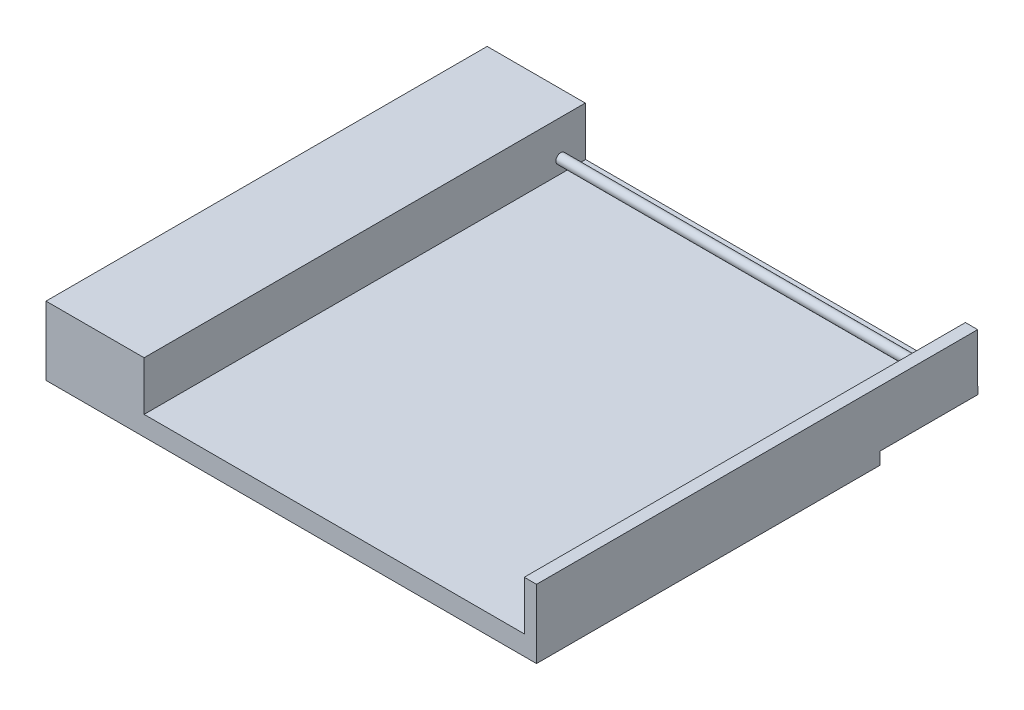
SolidWorks part; units mm, degrees
ref_plane "Front Plane" through (0, 0, 0) normal (0, 0, 1) x (1, 0, 0)
ref_plane "Top Plane" through (0, 0, 0) normal (0, 1, 0) x (1, 0, 0)
ref_plane "Right Plane" through (0, 0, 0) normal (1, 0, 0) x (0, 0, -1)
sketch "Sketch1" plane through (0, 0, 0) normal (0, 1, 0) x (1, 0, 0)
  line L1 (-100, -90) -> (100, -90)
  line L2 (-100, -90) -> (-100, 90)
  line L3 (-100, 90) -> (100, 90)
  line L4 (100, -90) -> (100, 90)
  line L5 (-100, -90) -> (100, 90) construction
  line L6 (-100, 90) -> (100, -90) construction
  point P0 (0, 0)
  dimension "D1" = 200
  dimension "D2" = 180
extrude "Boss-Extrude1" add sketch "Sketch1" along normal blind 3
sketch "Sketch2" plane through (0, 0, 0) normal (0, -1, 0) x (1, 0, 0)
  line L0 (-100, 90) -> (100, 90)
  line L1 (-100, 90) -> (-100, -50)
  line L2 (100, 90) -> (100, -50)
  line L3 (-100, -50) -> (100, -50)
  dimension "D1" = 140
extrude "Boss-Extrude2" add sketch "Sketch2" along normal blind 5
sketch "Sketch6" plane through (0, 3, 0) normal (0, 1, 0) x (1, 0, 0)
  line L0 (-100, -90) -> (100, -90)
  line L1 (-100, -90) -> (-100, 89.8697)
  line L2 (100, -90) -> (100, 89.8697)
  line L3 (-100, 89.8697) -> (100, 89.8697)
extrude "Boss-Extrude3" add sketch "Sketch6" along normal blind 20
sketch "Sketch7" plane through (0, 0, -89.8697) normal (0, 0, -1) x (-1, 0, 0)
  line L0 (-100, 13) -> (100, 13) construction
  line L1 (-100, 23) -> (-100, 3) construction
  line L2 (100, 23) -> (100, 3) construction
  line L3 (-100, 23) -> (100, 23) construction
  line L4 (-95, 3) -> (60, 3)
  line L5 (-95, 3) -> (-95, 23)
  line L6 (-95, 23) -> (60, 23)
  line L7 (60, 3) -> (60, 23)
  line L8 (-95, 3) -> (60, 23) construction
  line L9 (-95, 23) -> (60, 3) construction
  point P6 (-17.5, 13)
  dimension "D1" = 155
  dimension "D2" = 5
extrude "Cut-Extrude1" cut sketch "Sketch7" against normal up to surface (179.8697 mm away) up to face at (0, 9, 90)
sketch "Sketch8" plane through (95, 0, 0) normal (-1, 0, 0) x (0, 0, 1)
  line L0 (90, 3) -> (-89.8697, 3) construction
  line L1 (-89.8697, 23) -> (-89.8697, 3) construction
  circle A0 centre (-79.8697, 8.5) radius 2
  point P4 (0, 0)
  point P6 (0, 0)
  dimension "D3" = 4
  dimension "D1" = 5.5
  dimension "D2" = 10
extrude "Boss-Extrude4" add sketch "Sketch8" along normal up to surface (155 mm away) up to face at (-60, 13, 0.0651)
